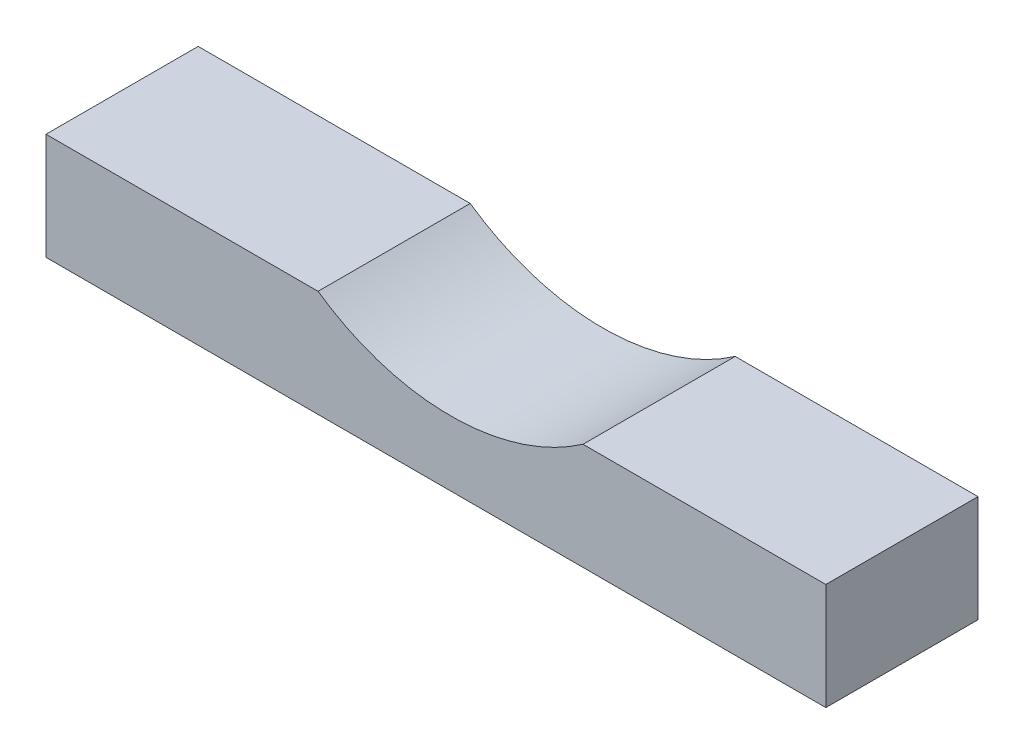
SolidWorks part; units mm, degrees
ref_plane "Front Plane" through (0, 0, 0) normal (0, 0, 1) x (1, 0, 0)
ref_plane "Top Plane" through (0, 0, 0) normal (0, 1, 0) x (1, 0, 0)
ref_plane "Right Plane" through (0, 0, 0) normal (1, 0, 0) x (0, 0, -1)
sketch "Sketch1" plane through (0, 0, 0) normal (0, 0, 1) x (1, 0, 0)
  line L1 (33.1703, -47.6274) -> (93.9679, -47.6274)
  line L2 (93.9679, -74.3328) -> (93.9679, -47.6274)
  line L3 (93.9679, -74.3328) -> (-101.288, -74.3328)
  line L4 (-101.288, -74.3328) -> (-101.288, -47.6274)
  line L5 (-101.288, -47.6274) -> (-33.1703, -47.6274)
  line L6 (-33.1703, -47.6274) -> (33.1703, -47.6274) construction
  arc A1 (-33.1703, -47.6274) -> (33.1703, -47.6274) centre (0, 0) ccw
extrude "Boss-Extrude1" add sketch "Sketch1" against normal up to surface (38.1 mm away) contours L5 A1 L1 L2 L3 L4
